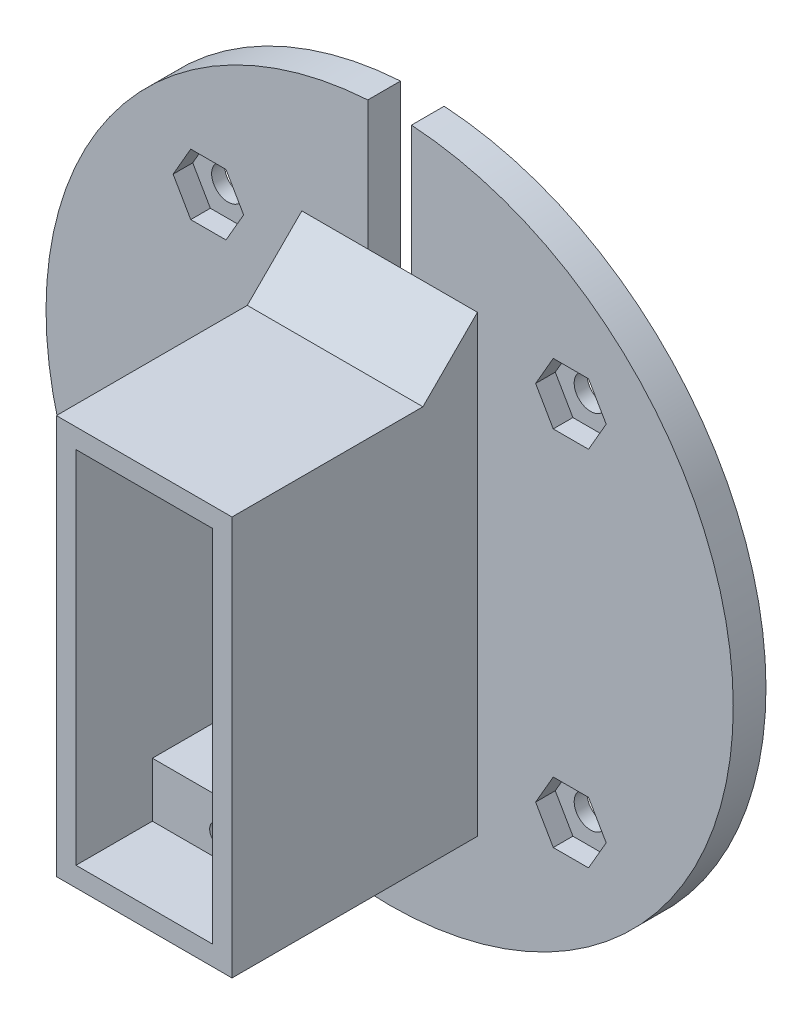
SolidWorks part; units mm, degrees
ref_plane "Alzado" through (0, 0, 0) normal (0, 0, 1) x (1, 0, 0)
ref_plane "Planta" through (0, 0, 0) normal (0, 1, 0) x (1, 0, 0)
ref_plane "Vista lateral" through (0, 0, 0) normal (1, 0, 0) x (0, 0, -1)
sketch "Croquis1" plane through (0, 0, 0) normal (0, 0, 1) x (1, 0, 0)
  circle A0 centre (-51.2357, 9.7866) radius 31.5
  dimension "D1" = 63
extrude "Saliente-Extruir1" add sketch "Croquis1" along normal blind 2.4
sketch "Croquis2" plane through (0, 0, 2.4) normal (0, 0, 1) x (1, 0, 0)
  line L0 (-51.2357, 9.7866) -> (-51.2357, -21.7134) construction
  line L1 (-51.2357, 9.7866) -> (-51.2357, 15.7866) construction
  line L2 (-51.2357, 15.7866) -> (-51.2357, 20.7866) construction
  line L3 (-51.2357, 20.7866) -> (-51.2357, 22.5866) construction
  line L4 (-51.2357, 22.5866) -> (-57.4857, 22.5866) construction
  line L6 (-57.4857, 22.5866) -> (-44.9857, 22.5866)
  line L7 (-57.4857, 22.5866) -> (-57.4857, -10.4134)
  line L8 (-57.4857, -10.4134) -> (-44.9857, -10.4134)
  line L9 (-44.9857, 22.5866) -> (-44.9857, -10.4134)
  line L14 (-59.2857, 24.3866) -> (-43.1857, 24.3866)
  line L15 (-59.2857, 24.3866) -> (-59.2857, -12.2134)
  line L16 (-59.2857, -12.2134) -> (-43.1857, -12.2134)
  line L17 (-43.1857, 24.3866) -> (-43.1857, -12.2134)
  circle A0 centre (-51.2357, 9.7866) radius 31.5 construction
  dimension "D1" = 6
  dimension "D2" = 5
  dimension "D3" = 1.8
  dimension "D4" = 6.25
  dimension "D5" = 12.5
  dimension "D6" = 33
  dimension "D7" = 1.8
  dimension "D8" = 1.8
  dimension "D9" = 1.8
  dimension "D10" = 1.8
extrude "Saliente-Extruir2" add sketch "Croquis2" along normal blind 22.5
sketch "Croquis5" plane through (0, 0, 2.4) normal (0, 0, 1) x (1, 0, 0)
  line L1 (-59.2857, 24.3866) -> (-43.1857, 24.3866)
  line L2 (-59.2857, 24.3866) -> (-59.2857, -12.2134)
  line L3 (-59.2857, -12.2134) -> (-43.1857, -12.2134)
  line L4 (-43.1857, 24.3866) -> (-43.1857, -12.2134)
extrude "Cortar-Extruir2" cut sketch "Croquis5" against normal blind 9
sketch "Croquis6" plane through (0, 0, 0) normal (0, 0, -1) x (-1, 0, 0)
  line L6 (51.2357, 9.7866) -> (73.5095, 32.0605) construction
  line L7 (73.5095, 32.0605) -> (73.5095, -12.4873) construction
  line L8 (73.5095, -12.4873) -> (28.9618, 32.0605) construction
  line L9 (28.9618, 32.0605) -> (28.9618, -12.4873) construction
  line L10 (28.9618, -12.4873) -> (51.2357, 9.7866) construction
  line L11 (51.2357, 24.3866) -> (53.2357, 24.3866)
  line L12 (43.1857, 24.3866) -> (59.2857, 24.3866) construction
  line L13 (53.2357, 24.3866) -> (53.2357, 44.3866)
  line L14 (53.2357, 44.3866) -> (49.2357, 44.3866)
  line L15 (49.2357, 44.3866) -> (49.2357, 24.3866)
  line L16 (49.2357, 24.3866) -> (51.2357, 24.3866)
  circle A0 centre (51.2357, 9.7866) radius 31.5 construction
  circle A1 centre (34.6187, 26.4036) radius 1.5
  circle A2 centre (67.8527, 26.4036) radius 1.5
  circle A3 centre (67.8527, -6.8304) radius 1.5
  circle A4 centre (34.6187, -6.8304) radius 1.5
  dimension "D3" = 8
  dimension "D1" = 20
  dimension "D2" = 4
extrude "Cortar-Extruir3" cut sketch "Croquis6" against normal blind 2.4
sketch "Croquis7" plane through (0, 22.5866, 0) normal (0, -1, 0) x (1, 0, 0)
  line L0 (-57.4857, 24.9) -> (-57.4857, 2.4) construction
  line L1 (-57.4857, 17.9) -> (-44.9857, 17.9)
  line L2 (-57.4857, 17.9) -> (-57.4857, 8.9)
  line L3 (-57.4857, 8.9) -> (-44.9857, 8.9)
  line L4 (-44.9857, 17.9) -> (-44.9857, 8.9)
  line L5 (-44.9857, 24.9) -> (-44.9857, 2.4) construction
  line L6 (-44.9857, 24.9) -> (-57.4857, 24.9) construction
  dimension "D1" = 9
  dimension "D2" = 7
extrude "Saliente-Extruir3" add sketch "Croquis7" along normal up to vertex (33 mm away)
sketch "Croquis8" plane through (0, 0, 17.9) normal (0, 0, 1) x (1, 0, 0)
  line L0 (-44.9857, -10.4134) -> (-44.9857, 22.5866) construction
  line L1 (-44.9857, -5.4134) -> (-57.4857, -5.4134)
  line L2 (-44.9857, -5.4134) -> (-44.9857, 17.5866)
  line L4 (-57.4857, -5.4134) -> (-57.4857, 17.5866)
  line L5 (-57.4857, -10.4134) -> (-57.4857, 22.5866) construction
  line L6 (-44.9857, -10.4134) -> (-57.4857, -10.4134) construction
  line L9 (-44.9857, 17.5866) -> (-49.2357, 17.5866)
  line L10 (-49.2357, 17.5866) -> (-49.2357, 19.5866)
  line L11 (-49.2357, 19.5866) -> (-53.2357, 19.5866)
  line L12 (-53.2357, 19.5866) -> (-53.2357, 17.5866)
  line L13 (-53.2357, 17.5866) -> (-57.4857, 17.5866)
  line L14 (-44.9857, 22.5866) -> (-57.4857, 22.5866) construction
  circle A0 centre (-51.2357, -8.4134) radius 1
  circle A1 centre (-51.2357, 20.6366) radius 1
  dimension "D3" = 2
  dimension "D6" = 1.95
  dimension "D1" = 5
  dimension "D2" = 5
  dimension "D4" = 4
  dimension "D5" = 2
extrude "Cortar-Extruir5" cut sketch "Croquis8" against normal blind 9
sketch "Croquis9" plane through (-44.9857, 0, 0) normal (-1, 0, 0) x (0, 0, 1)
  line L0 (8.9, -5.4134) -> (3.9, -10.4134)
  line L1 (8.9, -10.4134) -> (2.4, -10.4134) construction
  line L2 (3.9, -10.4134) -> (8.9, -10.4134)
  line L3 (8.9, -10.4134) -> (8.9, -5.4134)
  line L4 (8.9, 17.5866) -> (3.9, 22.5866)
  line L5 (8.9, 22.5866) -> (2.4, 22.5866) construction
  line L6 (3.9, 22.5866) -> (8.9, 22.5866)
  line L7 (8.9, 22.5866) -> (8.9, 17.5866)
extrude "Saliente-Extruir4" add sketch "Croquis9" along normal up to vertex (12.5 mm away)
sketch "Croquis10" plane through (0, 0, 8.9) normal (0, 0, 1) x (1, 0, 0)
  line L1 (-53.2357, 17.5866) -> (-49.2357, 17.5866)
  line L2 (-53.2357, 17.5866) -> (-53.2357, 19.5866)
  line L3 (-53.2357, 19.5866) -> (-49.2357, 19.5866)
  line L4 (-49.2357, 17.5866) -> (-49.2357, 19.5866)
extrude "Cortar-Extruir6" cut sketch "Croquis10" against normal blind 9
sketch "Croquis11" plane through (0, 0, 2.4) normal (0, 0, -1) x (-1, 0, 0)
  line L0 (49.2357, 24.3866) -> (43.1857, 24.3866)
  line L1 (43.1857, 24.3866) -> (43.1857, -12.2134)
  line L2 (43.1857, -12.2134) -> (59.2857, -12.2134)
  line L3 (59.2857, -12.2134) -> (59.2857, 24.3866)
  line L4 (59.2857, 24.3866) -> (53.2357, 24.3866)
  line L5 (53.2357, 24.3866) -> (53.2357, 22.5866)
  line L6 (44.9857, 22.5866) -> (57.4857, 22.5866) construction
  line L7 (53.2357, 22.5866) -> (57.4857, 22.5866)
  line L8 (57.4857, 22.5866) -> (57.4857, 10.5866)
  line L9 (57.4857, 22.5866) -> (57.4857, -10.4134) construction
  line L10 (57.4857, 10.5866) -> (44.9857, 10.5866)
  line L11 (44.9857, -10.4134) -> (44.9857, 22.5866) construction
  line L12 (44.9857, 10.5866) -> (44.9857, 22.5866)
  line L13 (44.9857, 22.5866) -> (49.2357, 22.5866)
  line L14 (49.2357, 22.5866) -> (49.2357, 24.3866)
extrude "Saliente-Extruir5" add sketch "Croquis11" along normal up to vertex (2.4 mm away)
sketch "Croquis12" plane through (-43.1857, 0, 0) normal (1, 0, 0) x (0, 0, -1)
  line L0 (-2.4, 24.3866) -> (-7.4, 24.3866)
  line L1 (-24.9, 24.3866) -> (-2.4, 24.3866) construction
  line L2 (-7.4, 24.3866) -> (-2.4, 29.3866)
  line L3 (-2.4, 29.3866) -> (-2.4, 24.3866)
extrude "Saliente-Extruir6" add sketch "Croquis12" against normal up to vertex (16.1 mm away)
sketch "Croquis13" plane through (0, 0, 2.4) normal (0, 0, 1) x (1, 0, 0)
  line L1 (-31.3855, -6.8304) -> (-33.0021, -4.0304)
  line L2 (-33.0021, -4.0304) -> (-36.2352, -4.0304)
  line L3 (-36.2352, -4.0304) -> (-37.8518, -6.8304)
  line L4 (-37.8518, -6.8304) -> (-36.2352, -9.6304)
  line L5 (-36.2352, -9.6304) -> (-33.0021, -9.6304)
  line L6 (-33.0021, -9.6304) -> (-31.3855, -6.8304)
  line L7 (-64.6195, -6.8304) -> (-66.2361, -4.0304)
  line L8 (-66.2361, -4.0304) -> (-69.4693, -4.0304)
  line L9 (-69.4693, -4.0304) -> (-71.0858, -6.8304)
  line L10 (-71.0858, -6.8304) -> (-69.4693, -9.6304)
  line L11 (-69.4693, -9.6304) -> (-66.2361, -9.6304)
  line L12 (-66.2361, -9.6304) -> (-64.6195, -6.8304)
  line L13 (-37.8518, 26.4036) -> (-36.2352, 23.6036)
  line L14 (-36.2352, 23.6036) -> (-33.0021, 23.6036)
  line L15 (-33.0021, 23.6036) -> (-31.3855, 26.4036)
  line L16 (-31.3855, 26.4036) -> (-33.0021, 29.2036)
  line L17 (-33.0021, 29.2036) -> (-36.2352, 29.2036)
  line L18 (-36.2352, 29.2036) -> (-37.8518, 26.4036)
  line L19 (-71.0858, 26.4036) -> (-69.4693, 23.6036)
  line L20 (-69.4693, 23.6036) -> (-66.2361, 23.6036)
  line L21 (-66.2361, 23.6036) -> (-64.6195, 26.4036)
  line L22 (-64.6195, 26.4036) -> (-66.2361, 29.2036)
  line L23 (-66.2361, 29.2036) -> (-69.4693, 29.2036)
  line L24 (-69.4693, 29.2036) -> (-71.0858, 26.4036)
  circle A0 centre (-34.6187, -6.8304) radius 2.8 construction
  circle A1 centre (-67.8527, -6.8304) radius 2.8 construction
  circle A2 centre (-34.6187, 26.4036) radius 2.8 construction
  circle A3 centre (-67.8527, 26.4036) radius 2.8 construction
  dimension "D1" = 5.6
  dimension "D2" = 5.6
extrude "Cortar-Extruir7" cut sketch "Croquis13" against normal blind 1.8
sketch "Croquis14" plane through (0, 0, 0) normal (0, 0, -1) x (-1, 0, 0)
  line L0 (53.2357, 41.223) -> (53.2357, 22.5866)
  line L1 (53.2357, 22.5866) -> (57.4857, 22.5866)
  line L2 (57.4857, 22.5866) -> (57.4857, 10.5866)
  line L3 (57.4857, 10.5866) -> (44.9857, 10.5866)
  line L4 (44.9857, 10.5866) -> (44.9857, 22.5866)
  line L5 (44.9857, 22.5866) -> (49.2357, 22.5866)
  line L6 (49.2357, 22.5866) -> (49.2357, 41.223)
  arc A0 (53.2357, 41.223) -> (49.2357, 41.223) centre (51.2357, 9.7866) cw
  circle A1 centre (67.8527, -6.8304) radius 1.5
  circle A2 centre (34.6187, -6.8304) radius 1.5
  circle A3 centre (34.6187, 26.4036) radius 1.5
  circle A4 centre (67.8527, 26.4036) radius 1.5
extrude "Saliente-Extruir7" add sketch "Croquis14" along normal blind 0.6
